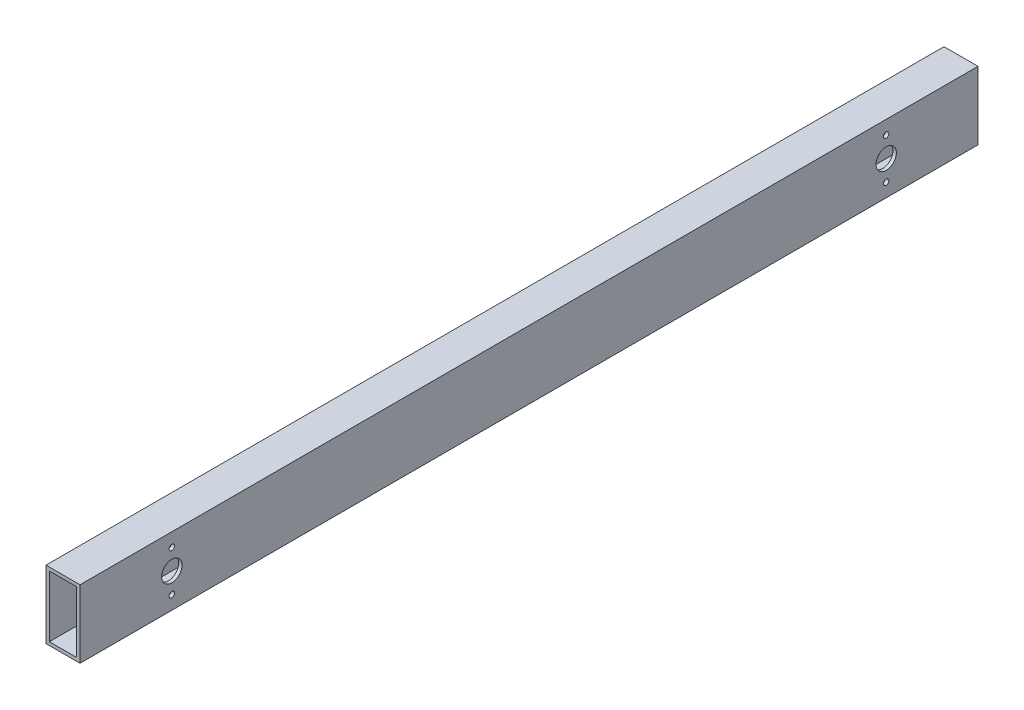
SolidWorks part; units mm, degrees
ref_plane "Front Plane" through (0, 0, 0) normal (0, 0, 1) x (1, 0, 0)
ref_plane "Top Plane" through (0, 0, 0) normal (0, 1, 0) x (1, 0, 0)
ref_plane "Right Plane" through (0, 0, 0) normal (1, 0, 0) x (0, 0, -1)
sketch "Sketch1" plane through (0, 0, 0) normal (0, 0, 1) x (1, 0, 0)
  line L1 (-12.1647, 2.5103) -> (19.5853, 2.5103)
  line L2 (-12.1647, 2.5103) -> (-12.1647, -60.9897)
  line L3 (-12.1647, -60.9897) -> (19.5853, -60.9897)
  line L4 (19.5853, 2.5103) -> (19.5853, -60.9897)
  line L5 (-8.9897, -0.6647) -> (16.4103, -0.6647)
  line L6 (-8.9897, -0.6647) -> (-8.9897, -57.8147)
  line L7 (-8.9897, -57.8147) -> (16.4103, -57.8147)
  line L8 (16.4103, -0.6647) -> (16.4103, -57.8147)
  dimension "D1" = 63.5
  dimension "D2" = 31.75
  dimension "D3" = 3.175
  dimension "D4" = 3.175
  dimension "D5" = 3.175
  dimension "D6" = 3.175
extrude "Boss-Extrude1" add sketch "Sketch1" along normal blind 838.2
sketch "Sketch2" plane through (19.5853, 0, 0) normal (1, 0, 0) x (0, 0, -1)
  line L0 (-838.2, 2.5103) -> (0, 2.5103) construction
  line L2 (-838.2, -60.9897) -> (-838.2, 2.5103) construction
  line L3 (-838.2, -60.9897) -> (0, -60.9897) construction
  line L4 (-419.1, 2.5103) -> (-419.1, -60.9897)
  circle A0 centre (-752.475, -29.2397) radius 9.525
  circle A1 centre (-752.475, -48.2897) radius 2.54
  circle A2 centre (-752.475, -10.1897) radius 2.54
  circle A3 centre (-85.725, -48.2897) radius 2.54
  circle A4 centre (-85.725, -29.2397) radius 9.525
  circle A5 centre (-85.725, -10.1897) radius 2.54
  dimension "D1" = 19.05
  dimension "D8" = 5.08
  dimension "D9" = 5.08
  dimension "D2" = 31.75
  dimension "D3" = 85.725
  dimension "D4" = 0
  dimension "D5" = 0
  dimension "D6" = 12.7
  dimension "D7" = 12.7
  dimension "D10" = 419.1
extrude "Cut-Extrude1" cut sketch "Sketch2" against normal up to surface (31.75 mm away) contours A0 | A2 | A1 | A5 | A4 | A3 up to face at (-12.1647, -29.2397, 419.1)
